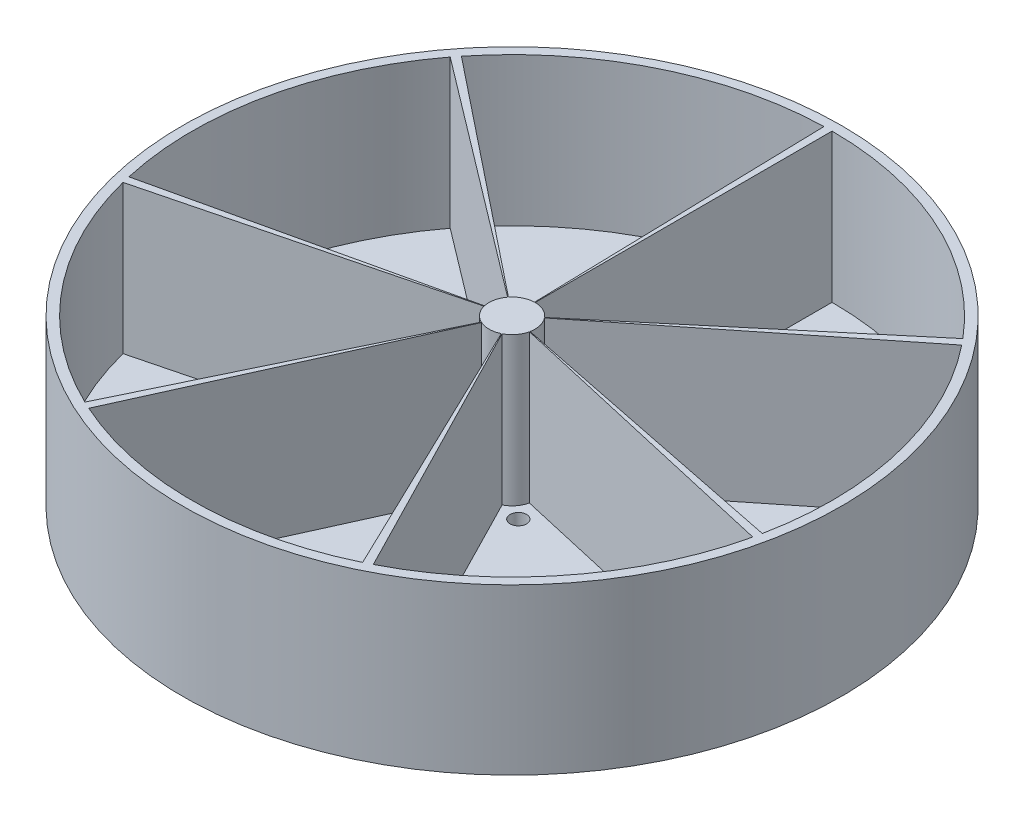
SolidWorks part; units mm, degrees
ref_plane "Front Plane" through (0, 0, 0) normal (0, 0, 1) x (1, 0, 0)
ref_plane "Top Plane" through (0, 0, 0) normal (0, 1, 0) x (1, 0, 0)
ref_plane "Right Plane" through (0, 0, 0) normal (1, 0, 0) x (0, 0, -1)
sketch "Sketch1" plane through (0, 0, 0) normal (0, 0, 1) x (1, 0, 0)
  line L1 (0, 0) -> (100, 0)
  line L2 (0, 0) -> (0, 50)
  line L3 (0, 50) -> (100, 50)
  line L4 (100, 0) -> (100, 50)
  dimension "D1" = 100
  dimension "D2" = 50
revolve "Revolve1" add sketch "Sketch1" angle 360 about L2
sketch "Sketch2" plane through (0, 50, 0) normal (0, 1, 0) x (1, 0, 0)
  line L0 (0, 7) -> (0, 97.0922)
  line L1 (5.3623, 4.4995) -> (74.3769, 62.4096)
  line L2 (5.4728, 4.3644) -> (75.9097, 60.536)
  line L3 (6.8612, -1.387) -> (95.1671, -19.2384)
  line L4 (6.8245, -1.5576) -> (94.6579, -21.605)
  line L5 (3.1935, -6.2291) -> (44.2945, -86.3996)
  line L6 (3.0372, -6.3068) -> (42.1267, -87.477)
  line L7 (-2.879, -6.3805) -> (-39.9328, -88.5001)
  line L8 (-3.0372, -6.3068) -> (-42.1267, -87.477)
  line L9 (-6.7835, -1.7273) -> (-94.0898, -23.9582)
  line L10 (-6.8245, -1.5576) -> (-94.6579, -21.605)
  line L11 (-5.5799, 4.2266) -> (-77.3953, 58.6247)
  line L12 (-5.4728, 4.3644) -> (-75.9097, 60.536)
  line L13 (-0.1745, 6.9978) -> (-2.4206, 97.062)
  arc A0 (74.3769, 62.4096) -> (0, 97.0922) centre (0, 0) ccw
  arc A1 (5.3623, 4.4995) -> (0, 7) centre (0, 0) ccw
  arc A2 (6.8612, -1.387) -> (5.4728, 4.3644) centre (0, 0) ccw
  arc A3 (95.1671, -19.2384) -> (75.9097, 60.536) centre (0, 0) ccw
  arc A4 (3.1935, -6.2291) -> (6.8245, -1.5576) centre (0, 0) ccw
  arc A5 (44.2945, -86.3996) -> (94.6579, -21.605) centre (0, 0) ccw
  arc A6 (-2.879, -6.3805) -> (3.0372, -6.3068) centre (0, 0) ccw
  arc A7 (-39.9328, -88.5001) -> (42.1267, -87.477) centre (0, 0) ccw
  arc A8 (-6.7835, -1.7273) -> (-3.0372, -6.3068) centre (0, 0) ccw
  arc A9 (-94.0898, -23.9582) -> (-42.1267, -87.477) centre (0, 0) ccw
  arc A10 (-5.5799, 4.2266) -> (-6.8245, -1.5576) centre (0, 0) ccw
  arc A11 (-77.3953, 58.6247) -> (-94.6579, -21.605) centre (0, 0) ccw
  arc A12 (-0.1745, 6.9978) -> (-5.4728, 4.3644) centre (0, 0) ccw
  arc A13 (-2.4206, 97.062) -> (-75.9097, 60.536) centre (0, 0) ccw
  point P32 (0, 0)
  dimension "D2" = 14
  dimension "D1" = 50
  dimension "D3" = 7
extrude "Cut-Extrude4" cut sketch "Sketch2" against normal blind 45
sketch "Sketch3" plane through (0, 0, 0) normal (0, -1, 0) x (1, 0, 0)
  circle A0 centre (0, 11) radius 2.5
  circle A1 centre (9.382, 7.4819) radius 2.5
  circle A2 centre (12.481, -2.0468) radius 2.5
  circle A3 centre (6.9634, -10.4107) radius 2.5
  circle A4 centre (-3.016, -11.3116) radius 2.5
  circle A5 centre (-9.9424, -4.0712) radius 2.5
  circle A6 centre (-8.6001, 5.8584) radius 2.5
  point P18 (1.0383, -0.5)
  dimension "D2" = 5
  dimension "D1" = 11
  dimension "D3" = 7
extrude "Cut-Extrude5" cut sketch "Sketch3" against normal blind 10
